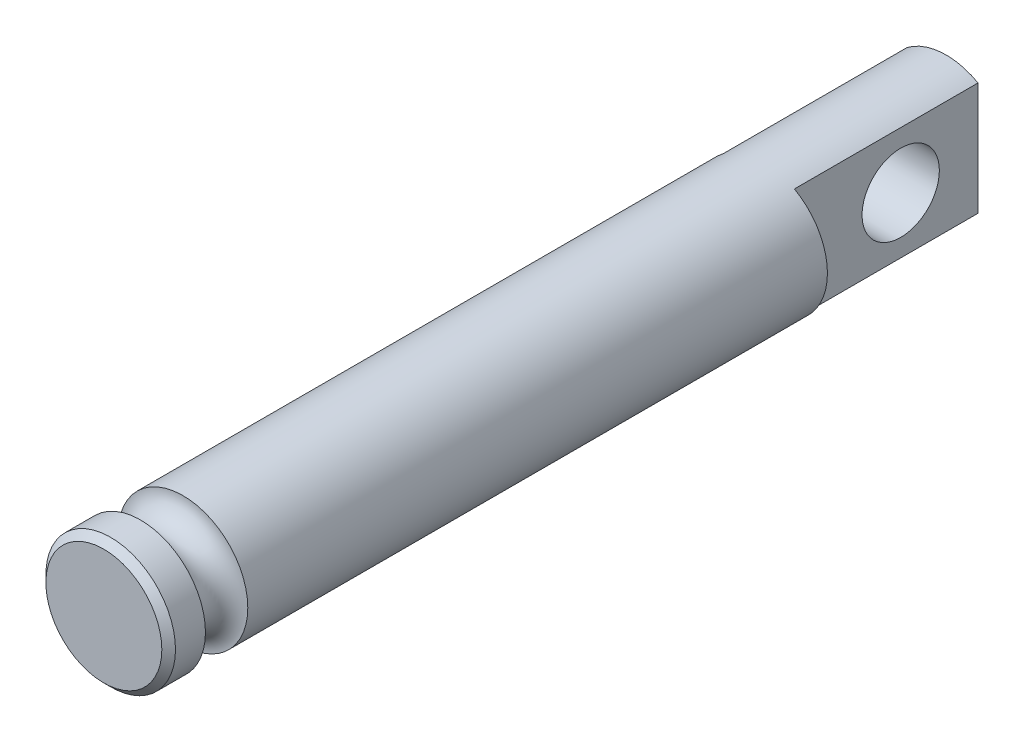
SolidWorks part; units mm, degrees
material "AISI 1045 Aço, trefilado"
ref_plane "Plano frontal" through (0, 0, 0) normal (0, 0, 1) x (1, 0, 0)
ref_plane "Plano superior" through (0, 0, 0) normal (0, 1, 0) x (1, 0, 0)
ref_plane "Plano direito" through (0, 0, 0) normal (1, 0, 0) x (0, 0, -1)
sketch "Esboço1" plane through (0, 0, 0) normal (1, 0, 0) x (0, 0, -1)
  line L0 (0, 0) -> (0, 6)
  line L1 (0, 6) -> (0.7071, 6.7071)
  line L2 (0.7071, 6.7071) -> (3.8089, 6.7071)
  line L3 (8.1911, 6.7071) -> (87.1911, 6.7071)
  line L4 (0, 0) -> (87.1911, 0)
  line L5 (87.1911, 0) -> (87.1911, 6.7071)
  arc A1 (3.8089, 6.7071) -> (8.1911, 6.7071) centre (6, 6.7071) ccw
  dimension "D1" = 6
  dimension "D2" = 1
  dimension "D3" = 45
  dimension "D5" = 79
revolve "Revolução1" add sketch "Esboço1" angle 360 about L4
sketch "Esboço2" plane through (0, 0, 0) normal (0, 1, 0) x (1, 0, 0)
  line L1 (6.7071, 87.1911) -> (3.2929, 87.1911)
  line L2 (6.7071, 87.1911) -> (6.7071, 68.1911)
  line L3 (6.7071, 68.1911) -> (3.2929, 68.1911)
  line L4 (3.2929, 87.1911) -> (3.2929, 68.1911)
  line L5 (-6.7071, 87.1911) -> (-4.0571, 87.1911)
  line L6 (-6.7071, 87.1911) -> (-6.7071, 68.1911)
  line L7 (-6.7071, 68.1911) -> (-4.0571, 68.1911)
  line L8 (-4.0571, 87.1911) -> (-4.0571, 68.1911)
  dimension "D1" = 19
  dimension "D2" = 19
  dimension "D3" = 10
  dimension "D4" = 7.35
extrude "Corte-extrusão1" cut sketch "Esboço2" against normal through all both and the other way through all contours L2 L1 L4 L3 | L6 L5 L8 L7
sketch "Esboço3" plane through (3.2929, 0, 0) normal (1, 0, 0) x (0, 0, -1)
  line L0 (87.1911, -5.8431) -> (87.1911, 5.8431) construction
  circle A0 centre (79.1911, 0) radius 4
  dimension "D1" = 8
  dimension "D2" = 8
extrude "Corte-extrusão2" cut sketch "Esboço3" against normal through all both and the other way through all
